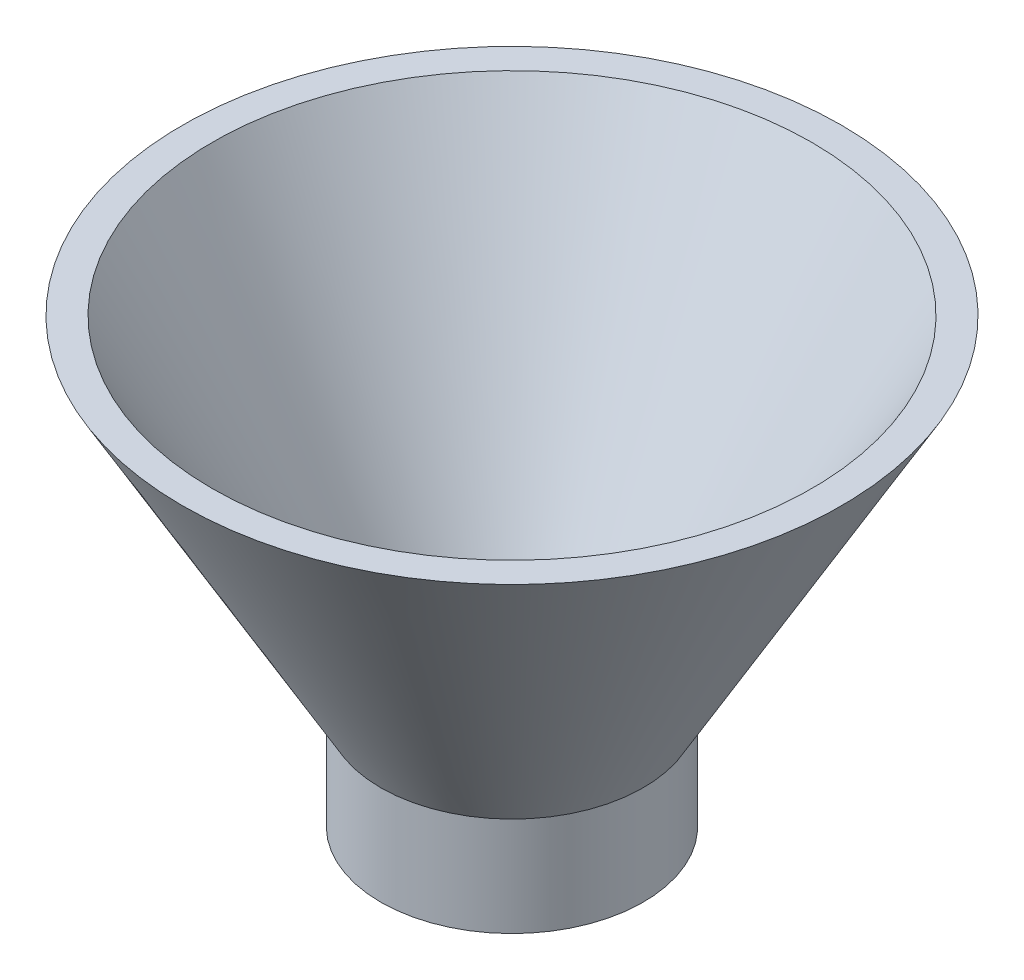
SolidWorks part; units mm, degrees
ref_plane "Front Plane" through (0, 0, 0) normal (0, 0, 1) x (1, 0, 0)
ref_plane "Top Plane" through (0, 0, 0) normal (0, 1, 0) x (1, 0, 0)
ref_plane "Right Plane" through (0, 0, 0) normal (1, 0, 0) x (0, 0, -1)
sketch "Sketch1" plane through (0, 0, 0) normal (0, 1, 0) x (1, 0, 0)
  circle A0 centre (0, 0) radius 13.25
  circle A1 centre (0, 0) radius 10.25
  dimension "D1" = 26.5
  dimension "D2" = 3
extrude "Boss-Extrude1" add sketch "Sketch1" along normal blind 10
sketch "Sketch2" plane through (0, 0, 0) normal (0, 0, 1) x (1, 0, 0)
  line L0 (0, 0) -> (0, 29.4274) construction
  line L1 (-13.25, 10) -> (-33.25, 44.641)
  line L3 (-30.25, 44.641) -> (-10.25, 10)
  line L4 (-10.25, 10) -> (-13.25, 10)
  line L5 (-13.25, 10) -> (-13.25, 42.4912) construction
  line L6 (-33.25, 44.641) -> (-30.25, 44.641)
  dimension "D1" = 40
  dimension "D2" = 30
revolve "Revolve1" add sketch "Sketch2" angle 360 about L0
fillet "Fillet1" radius 10 1 edges at (0, 10, -10.25)
